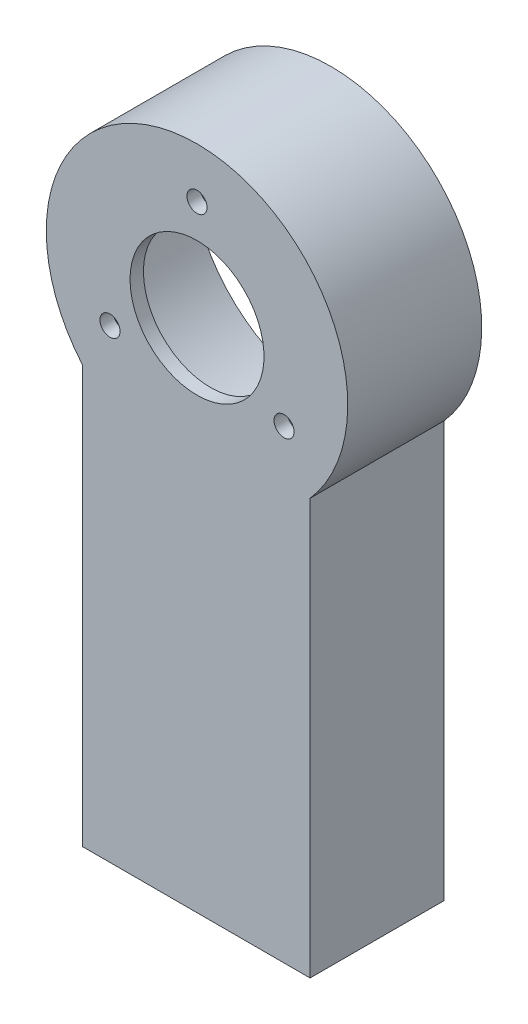
SolidWorks part; units mm, degrees
ref_plane "Front Plane" through (0, 0, 0) normal (0, 0, 1) x (1, 0, 0)
ref_plane "Top Plane" through (0, 0, 0) normal (0, 1, 0) x (1, 0, 0)
ref_plane "Right Plane" through (0, 0, 0) normal (1, 0, 0) x (0, 0, -1)
sketch "Sketch1" plane through (0, 0, 0) normal (0, 0, 1) x (1, 0, 0)
  line L1 (-17.1236, -14.5956) -> (-17.1236, -76.9)
  line L2 (16.8764, -14.8808) -> (16.8764, -76.9)
  line L3 (-17.1236, -76.9) -> (16.8764, -76.9)
  circle A0 centre (0, 0) radius 22.5
  arc A1 (-17.1236, -14.5956) -> (16.8764, -14.8808) centre (0, 0) ccw
  dimension "D1" = 45
  dimension "D2" = 76.9
  dimension "D3" = 34
extrude "Boss-Extrude1" add sketch "Sketch1" along normal blind 20 contours A0 L1 L3 L2 | A0 L1
sketch "Sketch2" plane through (0, 0, 0) normal (0, 0, -1) x (-1, 0, 0)
  circle A0 centre (0, 0) radius 10
  dimension "D1" = 20
extrude "Cut-Extrude1" cut sketch "Sketch2" against normal blind 20
sketch "Sketch3" plane through (0, 0, 0) normal (0, 0, -1) x (-1, 0, 0)
  circle A0 centre (0, 15) radius 1.5
  circle A1 centre (12.9904, -7.5) radius 1.5
  circle A2 centre (-12.9904, -7.5) radius 1.5
  point P10 (0, 0)
  dimension "D1" = 3
  dimension "D2" = 15
  dimension "D3" = 3
extrude "Cut-Extrude2" cut sketch "Sketch3" against normal blind 20
sketch "Sketch4" plane through (0, 0, 0) normal (0, 0, -1) x (-1, 0, 0)
  circle A0 centre (0, 0) radius 21
  dimension "D1" = 42
extrude "Cut-Extrude3" cut sketch "Sketch4" against normal blind 18
